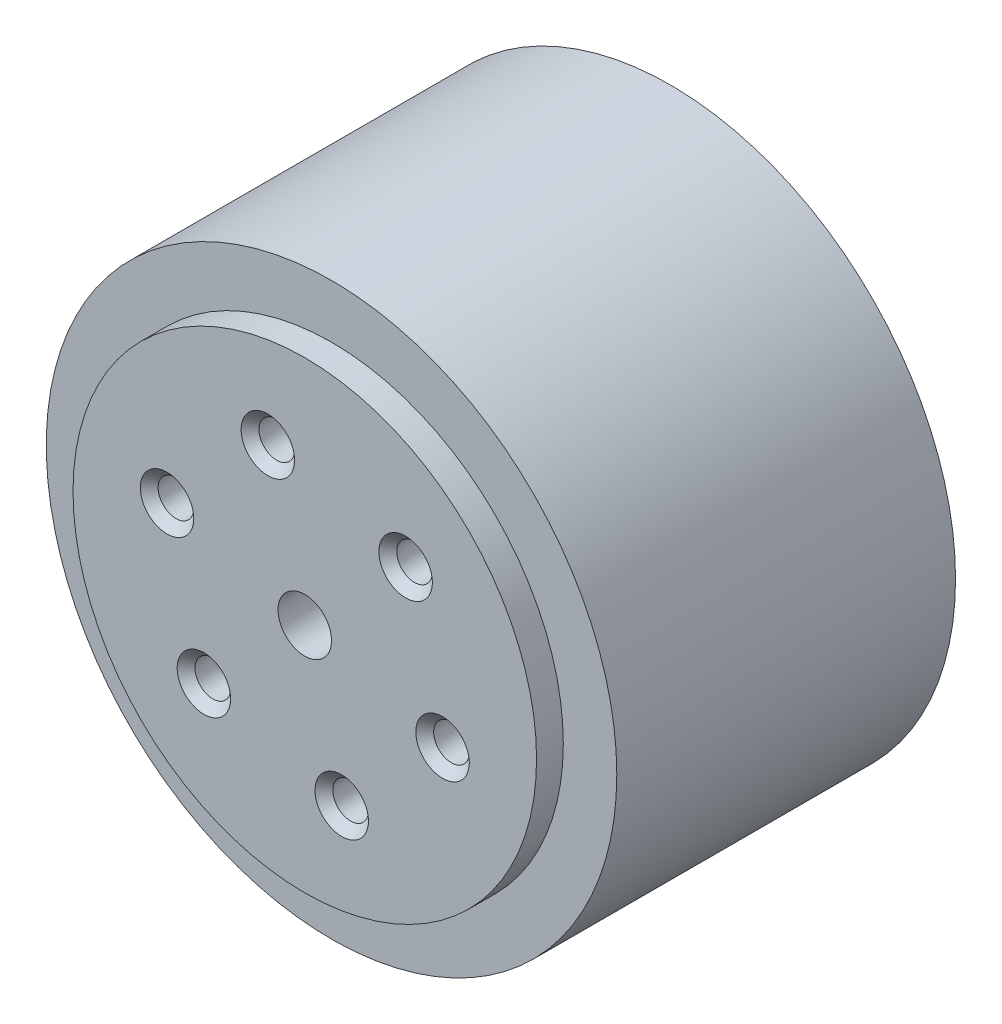
SolidWorks part; units mm, degrees
ref_plane "Alzado" through (0, 0, 0) normal (0, 0, 1) x (1, 0, 0)
ref_plane "Planta" through (0, 0, 0) normal (0, 1, 0) x (1, 0, 0)
ref_plane "Vista lateral" through (0, 0, 0) normal (1, 0, 0) x (0, 0, -1)
sketch "Croquis1" plane through (0, 0, 0) normal (0, 1, 0) x (1, 0, 0)
  line L0 (16, 10.1351) -> (0, 10.1351)
  line L1 (0, 10.1351) -> (0, -8.8649)
  line L2 (0, -8.8649) -> (16, -8.8649)
  line L3 (16, -8.8649) -> (16, 10.1351)
  line L4 (0, 10.1351) -> (0, -8.8649) construction
  dimension "D1" = 16
  dimension "D2" = 19
revolve "Revolución1" add sketch "Croquis1" angle 360 about L4
sketch "Croquis2" plane through (0, 0, 8.8649) normal (0, 0, 1) x (1, 0, 0)
  circle A0 centre (0, 0) radius 13
  dimension "D1" = 26
extrude "Saliente-Extruir1" add sketch "Croquis2" along normal blind 1.5
sketch "Croquis3" plane through (0, 0, -10.1351) normal (0, 0, -1) x (-1, 0, 0)
  circle A0 centre (0, 0) radius 13
  dimension "D1" = 26
extrude "Saliente-Extruir2" add sketch "Croquis3" along normal blind 1.5
hole_wizard "Taladro1" positions "Croquis5" profile "Croquis4" legacy end condition through all
sketch "Croquis5" plane through (0, 0, -11.6351) normal (0, 0, -1) x (-1, 0, 0)
  point P0 (0, 0)
  point P1 (0, 0)
sketch "Croquis4" plane through (0, 0, -11.6351) normal (1, 0, 0) x (0, 1, 0)
  line L0 (0, 0) -> (0, 22)
  line L1 (0, 22) -> (1.5, 22)
  line L2 (1.5, 22) -> (1.5, 15)
  line L3 (1.5, 15) -> (9, 15)
  line L4 (9, 15) -> (9, 0)
  line L5 (9, 0) -> (0, 0)
  line L6 (0, 110) -> (0, -10) construction
  dimension "Diámetro" = 3
  dimension "Profundidad" = 22
  dimension "Diámetro de refrentado 1" = 18
  dimension "Profundidad de refrentado 1" = 15
ref_plane "Plano1" through (-1.6583, 0, 0) normal (1, 0, 0) x (0, 0, -1)
hole_wizard "Diámetro de taladro Ø2.0 (2)1" positions "Croquis9" profile "Croquis8" hole size "Ø2.0" standard "Ansi Metric" end condition through all
sketch "Croquis9" plane through (0, 0, 10.3649) normal (0, 0, 1) x (1, 0, 0)
  line L0 (5.6569, 5.6569) -> (0, 0) construction
  point P1 (5.6569, 5.6569)
  point P17 (7.7274, -2.0706)
  point P18 (2.0706, -7.7274)
  point P19 (-5.6569, -5.6569)
  point P20 (-7.7274, 2.0706)
  point P21 (-2.0706, 7.7274)
  dimension "D1" = 8
  dimension "D2" = 6
sketch "Croquis8" plane through (5.6569, 5.6569, 10.3649) normal (1, 0, 0) x (0, -1, 0)
  line L0 (0, 0) -> (0, 22)
  line L1 (0, 22) -> (1, 22)
  line L2 (1, 22) -> (1, 0)
  line L5 (1, 0) -> (0, 0)
  line L11 (0, -6.35) -> (0, 107.95) construction
  dimension "Diámetro de taladro hasta el siguiente" = 2
  dimension "Profundidad de taladro hasta el siguiente" = 22
ref_plane "Plano2" through (1.6583, 0, 0) normal (-1, 0, 0) x (0, 0, 1)
sketch "Croquis10" plane through (0, 0, 0) normal (1, 0, 0) x (0, 0, -1)
  line L0 (-10.3649, 1.5) -> (-10.3649, -1.5) construction
  circle A0 centre (-6.8649, 0) radius 1.25
  dimension "D1" = 2.5
  dimension "D2" = 3.5
extrude "Cortar-Extruir1" cut sketch "Croquis10" against normal blind 6 and the other way blind 10
chamfer "Chaflán1" distance 0.5 angle 45 7 edges at (6.6569, 5.6569, 10.3649) (-9, 0, -11.6351) (8.7274, -2.0706, 10.3649) (3.0706, -7.7274, 10.3649) (-4.6569, -5.6569, 10.3649) (-6.7274, 2.0706, 10.3649) (-1.0706, 7.7274, 10.3649)
